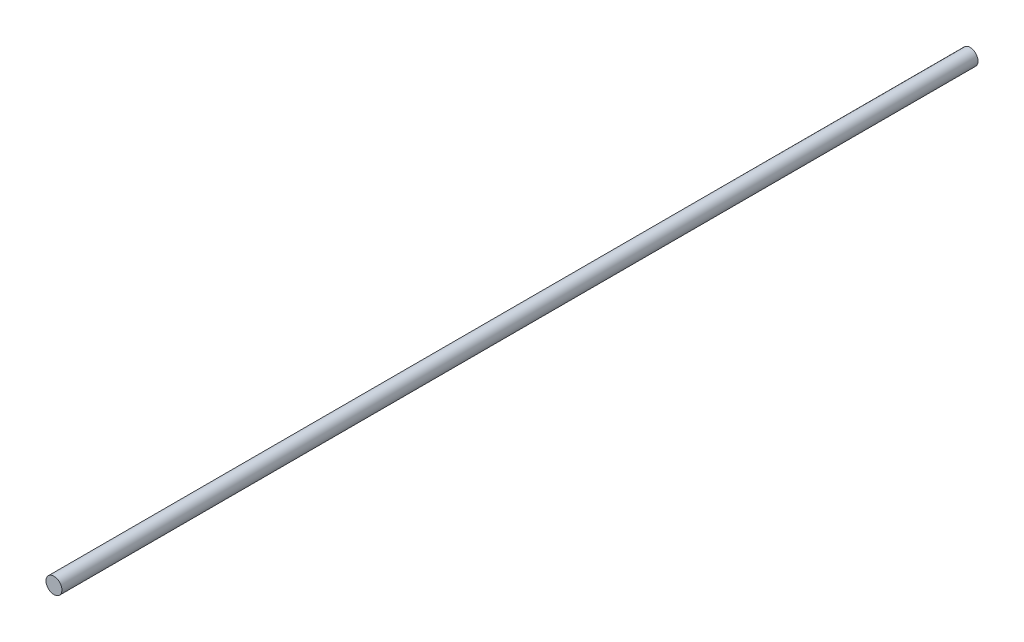
SolidWorks part; units mm, degrees
ref_plane "Płaszczyzna przednia" through (0, 0, 0) normal (0, 0, 1) x (1, 0, 0)
ref_plane "Płaszczyzna górna" through (0, 0, 0) normal (0, 1, 0) x (1, 0, 0)
ref_plane "Płaszczyzna prawa" through (0, 0, 0) normal (1, 0, 0) x (0, 0, -1)
sketch "Szkic1" plane through (0, 0, 0) normal (0, 0, 1) x (1, 0, 0)
  circle A0 centre (0, 0) radius 4
extrude "Dodanie-wyciągnięcie1" add sketch "Szkic1" along normal blind 460
